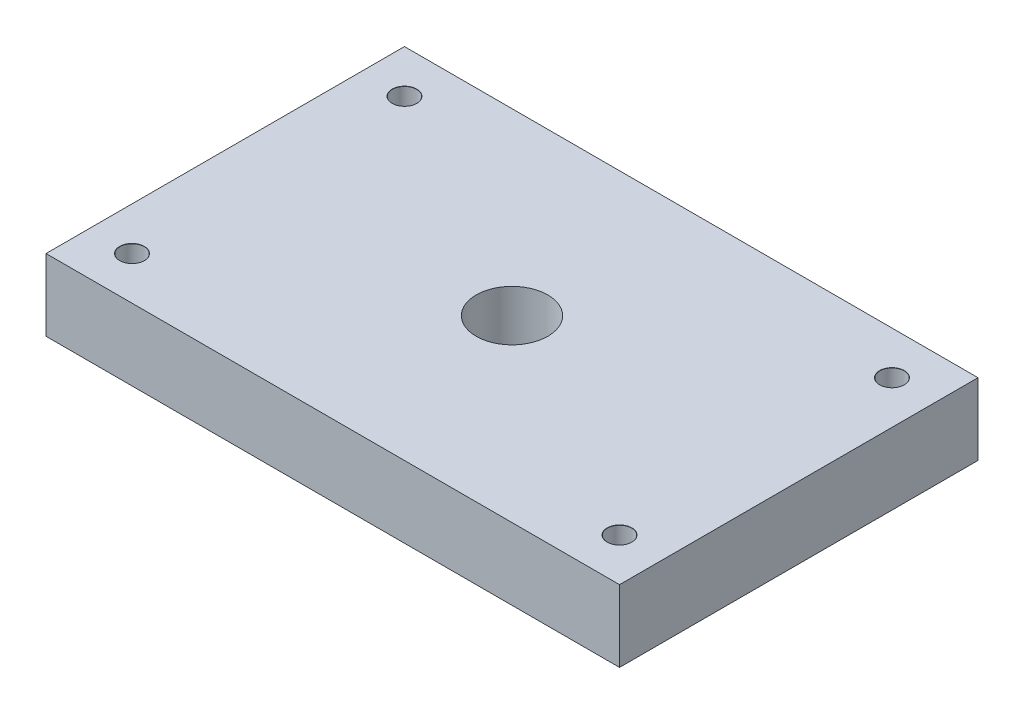
SolidWorks part; units mm, degrees
ref_plane "Front Plane" through (0, 0, 0) normal (0, 0, 1) x (1, 0, 0)
ref_plane "Top Plane" through (0, 0, 0) normal (0, 1, 0) x (1, 0, 0)
ref_plane "Right Plane" through (0, 0, 0) normal (1, 0, 0) x (0, 0, -1)
sketch "Sketch1" plane through (0, 0, 0) normal (0, 1, 0) x (1, 0, 0)
  line L1 (-40, -25) -> (40, -25)
  line L2 (-40, -25) -> (-40, 25)
  line L3 (-40, 25) -> (40, 25)
  line L4 (40, -25) -> (40, 25)
  line L5 (-40, -25) -> (40, 25) construction
  line L6 (-40, 25) -> (40, -25) construction
  point P0 (0, 0)
  dimension "D1" = 80
  dimension "D2" = 50
extrude "Boss-Extrude1" add sketch "Sketch1" along normal blind 10
sketch "Sketch2" plane through (0, 10, 0) normal (0, 1, 0) x (1, 0, 0)
  circle A0 centre (0, 0) radius 5
  dimension "D1" = 10
extrude "Cut-Extrude1" cut sketch "Sketch2" against normal through all
hole_wizard "M3 Clearance Hole1" positions "Sketch3" profile "Sketch4" hole size "M3" standard "ANSI Metric" end condition through all
sketch "Sketch3" plane through (0, 10, 0) normal (0, 1, 0) x (1, 0, 0)
  line L0 (-34, 19) -> (34, 19) construction
  line L1 (34, 19) -> (34, -19) construction
  line L2 (34, -19) -> (-34, -19) construction
  line L3 (-34, -19) -> (-34, 19) construction
  line L5 (40, 25) -> (-40, 25) construction
  line L6 (-40, -25) -> (40, -25) construction
  line L7 (-40, 25) -> (-40, -25) construction
  line L8 (40, -25) -> (40, 25) construction
  point P0 (-34, 19)
  point P2 (34, 19)
  point P4 (-34, -19)
  point P6 (34, -19)
  dimension "D1" = 6
  dimension "D2" = 6
  dimension "D3" = 6
  dimension "D4" = 6
sketch "Sketch4" plane through (-34, 10, -19) normal (1, 0, 0) x (0, 0, 1)
  line L0 (0, 0) -> (0, 10)
  line L1 (0, 10) -> (1.7, 10)
  line L2 (1.7, 10) -> (1.7, 0.025)
  line L3 (1.7, 0.025) -> (1.725, 0)
  line L5 (1.725, 0) -> (0, 0)
  line L6 (-1.7, 0.025) -> (-1.725, 0) construction
  line L11 (0, -6.35) -> (0, 107.95) construction
  dimension "Thru Hole Dia." = 3.4
  dimension "Thru Hole Depth" = 10
  dimension "Near C'Sink Dia." = 3.45
  dimension "Near C'Sink Angle" = 90
